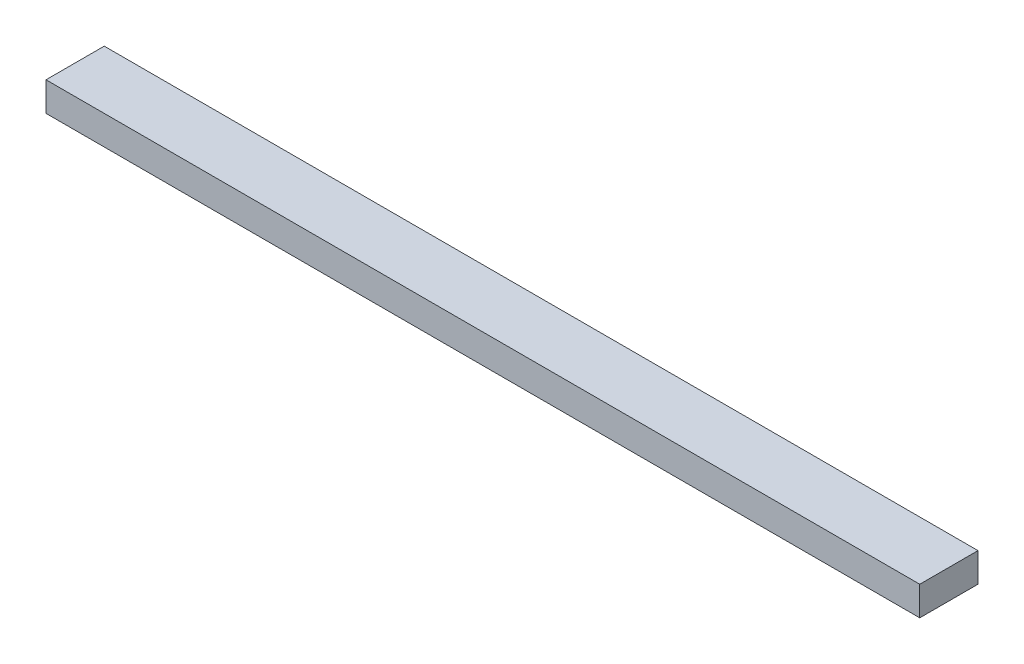
SolidWorks part; units mm, degrees
ref_plane "Front Plane" through (0, 0, 0) normal (0, 0, 1) x (1, 0, 0)
ref_plane "Top Plane" through (0, 0, 0) normal (0, 1, 0) x (1, 0, 0)
ref_plane "Right Plane" through (0, 0, 0) normal (1, 0, 0) x (0, 0, -1)
sketch "Sketch1" plane through (0, 0, 0) normal (0, 1, 0) x (1, 0, 0)
  line L1 (-15, -1) -> (15, -1)
  line L2 (-15, -1) -> (-15, 1)
  line L3 (-15, 1) -> (15, 1)
  line L4 (15, -1) -> (15, 1)
  line L5 (-15, -1) -> (15, 1) construction
  line L6 (-15, 1) -> (15, -1) construction
  point P0 (0, 0)
  dimension "D1" = 30
  dimension "D2" = 2
extrude "Boss-Extrude1" add sketch "Sketch1" along normal blind 1
